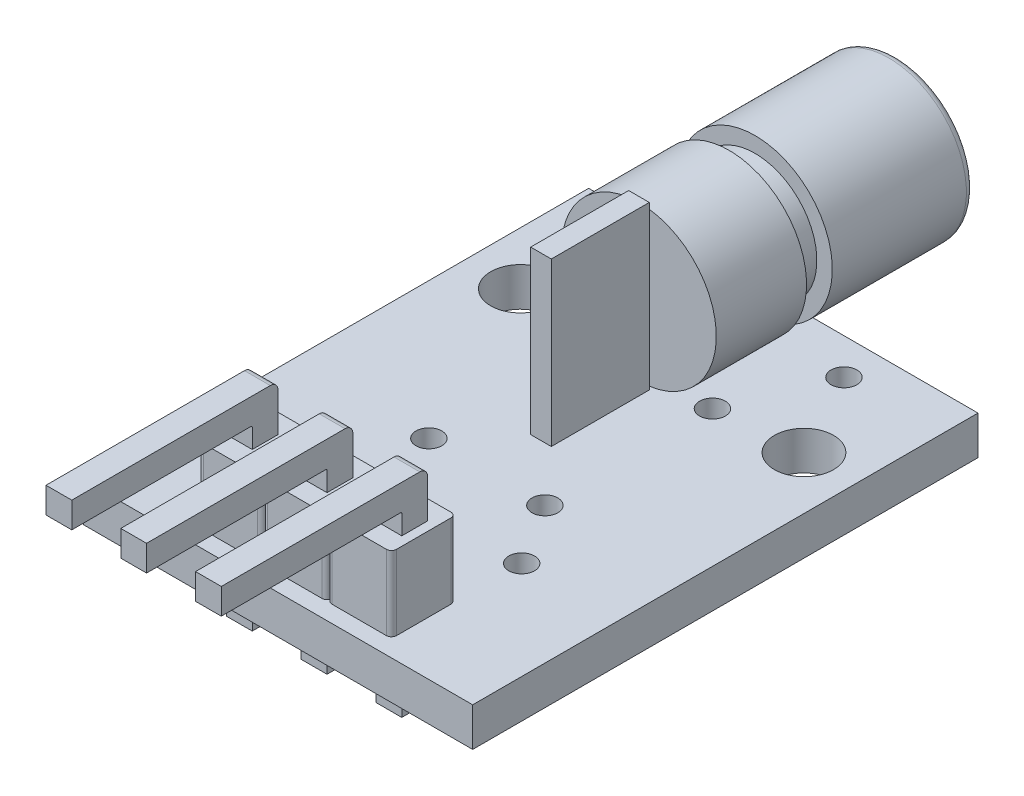
SolidWorks part; units mm, degrees
ref_plane "Front Plane" through (0, 0, 0) normal (0, 0, 1) x (1, 0, 0)
ref_plane "Top Plane" through (0, 0, 0) normal (0, 1, 0) x (1, 0, 0)
ref_plane "Right Plane" through (0, 0, 0) normal (1, 0, 0) x (0, 0, -1)
sketch "Sketch1" plane through (0, 0, 0) normal (0, 1, 0) x (1, 0, 0)
  line L1 (-7.55, -9.8) -> (7.55, -9.8)
  line L2 (-7.55, -9.8) -> (-7.55, 9.8)
  line L3 (-7.55, 9.8) -> (7.55, 9.8)
  line L4 (7.55, -9.8) -> (7.55, 9.8)
  line L5 (-7.55, -9.8) -> (7.55, 9.8) construction
  line L6 (-7.55, 9.8) -> (7.55, -9.8) construction
  point P0 (0, 0)
  dimension "D1" = 15.1
  dimension "D2" = 19.6
extrude "Boss-Extrude1" add sketch "Sketch1" along normal blind 1.5
sketch "Sketch2" plane through (0, 0, 0) normal (0, -1, 0) x (1, 0, 0)
  line L0 (0.5, 7.4) -> (3.4, 7.4) construction
  line L1 (-0.5, 8.4) -> (0.5, 8.4)
  line L2 (-0.5, 8.4) -> (-0.5, 7.4)
  line L3 (-0.5, 7.4) -> (0.5, 7.4)
  line L4 (0.5, 8.4) -> (0.5, 7.4)
  line L5 (-0.5, 8.4) -> (0.5, 7.4) construction
  line L6 (-0.5, 7.4) -> (0.5, 8.4) construction
  line L7 (3.4, 8.4) -> (2.4, 8.4)
  line L8 (3.4, 8.4) -> (3.4, 7.4)
  line L9 (3.4, 7.4) -> (2.4, 7.4)
  line L10 (2.4, 8.4) -> (2.4, 7.4)
  line L11 (3.4, 8.4) -> (2.4, 7.4) construction
  line L12 (3.4, 7.4) -> (2.4, 8.4) construction
  line L13 (-3.4, 8.4) -> (-2.4, 8.4)
  line L14 (-3.4, 8.4) -> (-3.4, 7.4)
  line L15 (-3.4, 7.4) -> (-2.4, 7.4)
  line L16 (-2.4, 8.4) -> (-2.4, 7.4)
  line L17 (-3.4, 8.4) -> (-2.4, 7.4) construction
  line L18 (-3.4, 7.4) -> (-2.4, 8.4) construction
  line L19 (-2.4, 7.4) -> (-0.5, 7.4) construction
  line L20 (0, 0) -> (0, 7.4) construction
  line L21 (-7.55, 9.8) -> (7.55, 9.8) construction
  line L22 (0.5, 8.4) -> (2.4, 8.4) construction
  line L23 (-2.4, 8.4) -> (-0.5, 8.4) construction
  point P0 (0, 7.9)
  point P5 (2.9, 7.9)
  point P10 (-2.9, 7.9)
  dimension "D1" = 1
  dimension "D2" = 1
  dimension "D3" = 2.4
  dimension "D4" = 5.8
extrude "Boss-Extrude2" add sketch "Sketch2" along normal blind 1.7
sketch "Sketch3" plane through (0, 1.5, 0) normal (0, 1, 0) x (1, 0, 0)
  line L0 (0.5, -8.4) -> (-0.5, -7.4) construction
  line L2 (-3.75, -9.15) -> (-3.75, -6.65)
  line L4 (3.75, -9.15) -> (3.75, -6.65)
  line L5 (-3.75, -9.15) -> (3.75, -6.65) construction
  line L6 (-3.75, -6.65) -> (3.75, -9.15) construction
  line L7 (-3.75, -6.65) -> (-1.45, -6.65)
  line L8 (-1.05, -6.65) -> (1.05, -6.65)
  line L9 (1.45, -6.65) -> (3.75, -6.65)
  line L10 (-1.05, -6.65) -> (-1.45, -6.65) construction
  line L11 (1.45, -6.65) -> (1.05, -6.65) construction
  line L12 (-3.75, -9.15) -> (-1.45, -9.15)
  line L13 (-1.05, -9.15) -> (1.05, -9.15)
  line L14 (1.45, -9.15) -> (3.75, -9.15)
  line L15 (-1.05, -9.15) -> (-1.45, -9.15) construction
  line L16 (1.45, -9.15) -> (1.05, -9.15) construction
  line L17 (-1.25, -8.95) -> (-1.25, -6.85) construction
  line L18 (1.25, -8.95) -> (1.25, -6.85) construction
  line L19 (1.25, -8.95) -> (-1.25, -8.95) construction
  line L20 (1.25, -6.85) -> (-1.25, -6.85) construction
  line L21 (0, -7.9) -> (0, -9.15) construction
  arc A0 (-1.45, -6.65) -> (-1.25, -6.85) centre (-1.45, -6.85) cw
  arc A1 (-1.25, -6.85) -> (-1.05, -6.65) centre (-1.05, -6.85) cw
  arc A2 (1.05, -6.65) -> (1.25, -6.85) centre (1.05, -6.85) cw
  arc A3 (1.25, -6.85) -> (1.45, -6.65) centre (1.45, -6.85) cw
  arc A4 (-1.45, -9.15) -> (-1.25, -8.95) centre (-1.45, -8.95) ccw
  arc A5 (-1.25, -8.95) -> (-1.05, -9.15) centre (-1.05, -8.95) ccw
  arc A6 (1.05, -9.15) -> (1.25, -8.95) centre (1.05, -8.95) ccw
  arc A7 (1.25, -8.95) -> (1.45, -9.15) centre (1.45, -8.95) ccw
  point P0 (0, -7.9)
  dimension "D3" = 0.2
  dimension "D4" = 0.2
  dimension "D1" = 7.5
  dimension "D2" = 2.5
extrude "Boss-Extrude3" add sketch "Sketch3" along normal blind 2.9
sketch "Sketch4" plane through (0, 4.4, 0) normal (0, 1, 0) x (1, 0, 0)
  line L1 (-3.4, -8.4) -> (-2.4, -8.4)
  line L2 (-3.4, -8.4) -> (-3.4, -7.4)
  line L3 (-3.4, -7.4) -> (-2.4, -7.4)
  line L4 (-2.4, -8.4) -> (-2.4, -7.4)
  line L5 (-0.5, -8.4) -> (0.5, -8.4)
  line L6 (-0.5, -8.4) -> (-0.5, -7.4)
  line L7 (-0.5, -7.4) -> (0.5, -7.4)
  line L8 (0.5, -8.4) -> (0.5, -7.4)
  line L9 (2.4, -8.4) -> (3.4, -8.4)
  line L10 (2.4, -8.4) -> (2.4, -7.4)
  line L11 (2.4, -7.4) -> (3.4, -7.4)
  line L12 (3.4, -8.4) -> (3.4, -7.4)
extrude "Boss-Extrude4" add sketch "Sketch4" along normal blind 1.8
sketch "Sketch5" plane through (0, 0, 8.4) normal (0, 0, 1) x (1, 0, 0)
  line L0 (-2.4, 6.2) -> (-2.4, 4.4) construction
  line L1 (-3.4, 6.2) -> (-2.4, 6.2)
  line L2 (-3.4, 6.2) -> (-3.4, 5.2)
  line L3 (-3.4, 5.2) -> (-2.4, 5.2)
  line L4 (-2.4, 6.2) -> (-2.4, 5.2)
  line L5 (0.5, 6.2) -> (0.5, 4.4) construction
  line L6 (-0.5, 6.2) -> (0.5, 6.2)
  line L7 (-0.5, 6.2) -> (-0.5, 5.2)
  line L8 (-0.5, 5.2) -> (0.5, 5.2)
  line L9 (0.5, 6.2) -> (0.5, 5.2)
  line L10 (3.4, 6.2) -> (3.4, 4.4) construction
  line L11 (2.4, 6.2) -> (3.4, 6.2)
  line L12 (2.4, 6.2) -> (2.4, 5.2)
  line L13 (2.4, 5.2) -> (3.4, 5.2)
  line L14 (3.4, 6.2) -> (3.4, 5.2)
  line L15 (-2.4, 5.2) -> (-0.5, 5.2) construction
  line L16 (0.5, 5.2) -> (2.4, 5.2) construction
extrude "Boss-Extrude5" add sketch "Sketch5" along normal blind 7
sketch "Sketch7" plane through (0, 1.5, 0) normal (0, 1, 0) x (1, 0, 0)
  line L0 (7.55, 9.8) -> (-7.55, 9.8) construction
  line L1 (0.4, 4.2) -> (-0.4, 4.2)
  line L2 (0.4, 4.2) -> (0.4, 0.4)
  line L3 (0.4, 0.4) -> (-0.4, 0.4)
  line L4 (-0.4, 4.2) -> (-0.4, 0.4)
  line L5 (0.4, 4.2) -> (-0.4, 0.4) construction
  line L6 (0.4, 0.4) -> (-0.4, 4.2) construction
  line L7 (0, 0) -> (0, 0.4) construction
  point P0 (0, 2.3)
  dimension "D1" = 9.4
  dimension "D2" = 3.8
  dimension "D3" = 0.8
extrude "Boss-Extrude6" add sketch "Sketch7" along normal blind 6.3
sketch "Sketch8" plane through (0, 0, -4.2) normal (0, 0, -1) x (-1, 0, 0)
  line L0 (0, 4.6) -> (0, 0) construction
  circle A0 centre (0, 4.6) radius 3
  dimension "D1" = 6
  dimension "D2" = 4.6
extrude "Boss-Extrude7" add sketch "Sketch8" along normal blind 3.5
sketch "Sketch9" plane through (0, 0, -7.7) normal (0, 0, -1) x (-1, 0, 0)
  circle A0 centre (0, 4.6) radius 2.4
  dimension "D1" = 4.8
extrude "Boss-Extrude8" add sketch "Sketch9" along normal blind 1
sketch "Sketch10" plane through (0, 0, -8.7) normal (0, 0, -1) x (-1, 0, 0)
  circle A0 centre (0, 4.6) radius 3
  circle A1 centre (0, 4.6) radius 3 construction
extrude "Boss-Extrude9" add sketch "Sketch10" along normal blind 5.5
fillet "Fillet1" radius 0.3 1 edges at (-3, 4.6, -14.2)
sketch "Sketch11" plane through (0, 0, -14.2) normal (0, 0, -1) x (-1, 0, 0)
  circle A0 centre (0, 4.6) radius 1.5
  dimension "D1" = 3
extrude "Cut-Extrude1" cut sketch "Sketch11" against normal blind 1
sketch "Sketch12" plane through (0, 1.5, 0) normal (0, 1, 0) x (1, 0, 0)
  line L0 (-5.5, 5.1) -> (5.5, 5.1) construction
  line L1 (7.55, 9.8) -> (-7.55, 9.8) construction
  line L2 (0, 5.1) -> (0, 0) construction
  circle A0 centre (-5.5, 5.1) radius 1.15
  circle A1 centre (5.5, 5.1) radius 1.15
  dimension "D2" = 2.3
  dimension "D1" = 4.7
  dimension "D3" = 11
extrude "Cut-Extrude2" cut sketch "Sketch12" against normal through all
sketch "Sketch13" plane through (0, 0, 0) normal (0, -1, 0) x (1, 0, 0)
  line L0 (2.25, 1.7) -> (-2.25, -4.8) construction
  line L1 (2.25, 1.7) -> (-2.25, 1.7) construction
  line L2 (2.25, 1.7) -> (2.25, -4.8) construction
  line L3 (2.25, -4.8) -> (-2.25, -4.8) construction
  line L4 (-2.25, 1.7) -> (-2.25, -4.8) construction
  line L5 (-2.25, 1.7) -> (2.25, -4.8) construction
  line L6 (7.55, -9.8) -> (-7.55, -9.8) construction
  line L7 (0, 0) -> (0, -4.8) construction
  circle A0 centre (-2.25, -4.8) radius 0.5
  circle A1 centre (2.25, -4.8) radius 0.5
  circle A2 centre (2.25, 1.7) radius 0.5
  circle A3 centre (-2.25, 1.7) radius 0.5
  dimension "D3" = 1
  dimension "D1" = 5
  dimension "D2" = 6.5
  dimension "D4" = 4.5
extrude "Cut-Extrude3" cut sketch "Sketch13" against normal up to next
sketch "Sketch14" plane through (0, 0, 0) normal (0, -1, 0) x (1, 0, 0)
  line L0 (0, 0) -> (0, -2.15) construction
  line L1 (-3.75, -8.4) -> (3.75, -8.4) construction
  line L2 (-3.75, -8.4) -> (-3.75, 4.1) construction
  line L3 (-3.75, 4.1) -> (3.75, 4.1) construction
  line L4 (3.75, -8.4) -> (3.75, 4.1) construction
  line L5 (-3.75, -8.4) -> (3.75, 4.1) construction
  line L6 (-3.75, 4.1) -> (3.75, -8.4) construction
  line L7 (7.55, -9.8) -> (-7.55, -9.8) construction
  circle A0 centre (3.75, 4.1) radius 0.5
  circle A1 centre (-3.75, 4.1) radius 0.5
  circle A2 centre (-3.75, -8.4) radius 0.5
  circle A3 centre (3.75, -8.4) radius 0.5
  point P0 (0, -2.15)
  dimension "D1" = 1
  dimension "D2" = 7.5
  dimension "D3" = 12.5
  dimension "D4" = 1.4
extrude "Cut-Extrude4" cut sketch "Sketch14" against normal up to next
fillet "Fillet2" radius 0.2 4 edges at (3.75, 2.95, 6.65) (3.75, 2.95, 9.15) (-3.75, 2.95, 9.15) (-3.75, 2.95, 6.65)
fillet "Fillet3" radius 0.05 3 edges at (-2.9, 5.2, 8.4) (0, 5.2, 8.4) (2.9, 5.2, 8.4)
fillet "Fillet5" radius 0.3 3 edges at (2.9, 6.2, 7.4) (-2.9, 6.2, 7.4) (0, 6.2, 7.4)
